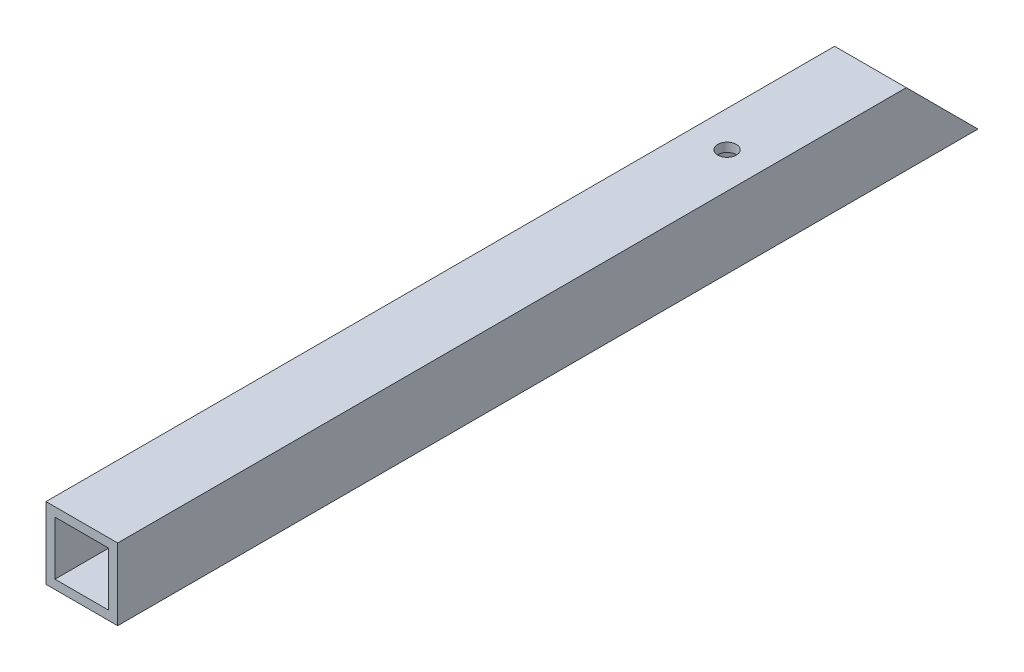
SolidWorks part; units mm, degrees
ref_plane "Front Plane" through (0, 0, 0) normal (0, 0, 1) x (1, 0, 0)
ref_plane "Top Plane" through (0, 0, 0) normal (0, 1, 0) x (1, 0, 0)
ref_plane "Right Plane" through (0, 0, 0) normal (1, 0, 0) x (0, 0, -1)
sketch "Sketch1" plane through (0, 0, 0) normal (0, 0, 1) x (1, 0, 0)
  line L0 (9.525, 9.525) -> (-9.525, 9.525)
  line L1 (12.7, -12.7) -> (-12.7, -12.7)
  line L2 (12.7, -12.7) -> (12.7, 12.7)
  line L3 (12.7, 12.7) -> (-12.7, 12.7)
  line L4 (-12.7, -12.7) -> (-12.7, 12.7)
  line L5 (12.7, -12.7) -> (-12.7, 12.7) construction
  line L6 (12.7, 12.7) -> (-12.7, -12.7) construction
  line L7 (-9.525, -9.525) -> (-9.525, 9.525)
  line L8 (9.525, -9.525) -> (-9.525, -9.525)
  line L9 (9.525, -9.525) -> (9.525, 9.525)
  point P0 (0, 0)
  dimension "D1" = 25.4
  dimension "D2" = 25.4
  dimension "D3" = 3.175
extrude "Boss-Extrude1" add sketch "Sketch1" along normal blind 304.8
sketch "Sketch2" plane through (12.7, 0, 0) normal (1, 0, 0) x (0, 0, -1)
  line L0 (0, 12.7) -> (0, -12.7)
  line L1 (0, -12.7) -> (-25.4, 12.7)
  line L2 (-304.8, 12.7) -> (0, 12.7) construction
  line L3 (-25.4, 12.7) -> (0, 12.7)
  line L4 (-304.8, -12.7) -> (0, -12.7) construction
  dimension "D1" = 45
extrude "Cut-Extrude1" cut sketch "Sketch2" against normal through all
sketch "Sketch3" plane through (0, 12.7, 0) normal (0, 1, 0) x (1, 0, 0)
  line L0 (-12.7, -25.4) -> (12.7, -25.4) construction
  circle A0 centre (0, -76.2) radius 3.302
  dimension "D1" = 6.604
  dimension "D2" = 50.8
extrude "Cut-Extrude2" cut sketch "Sketch3" against normal through all
